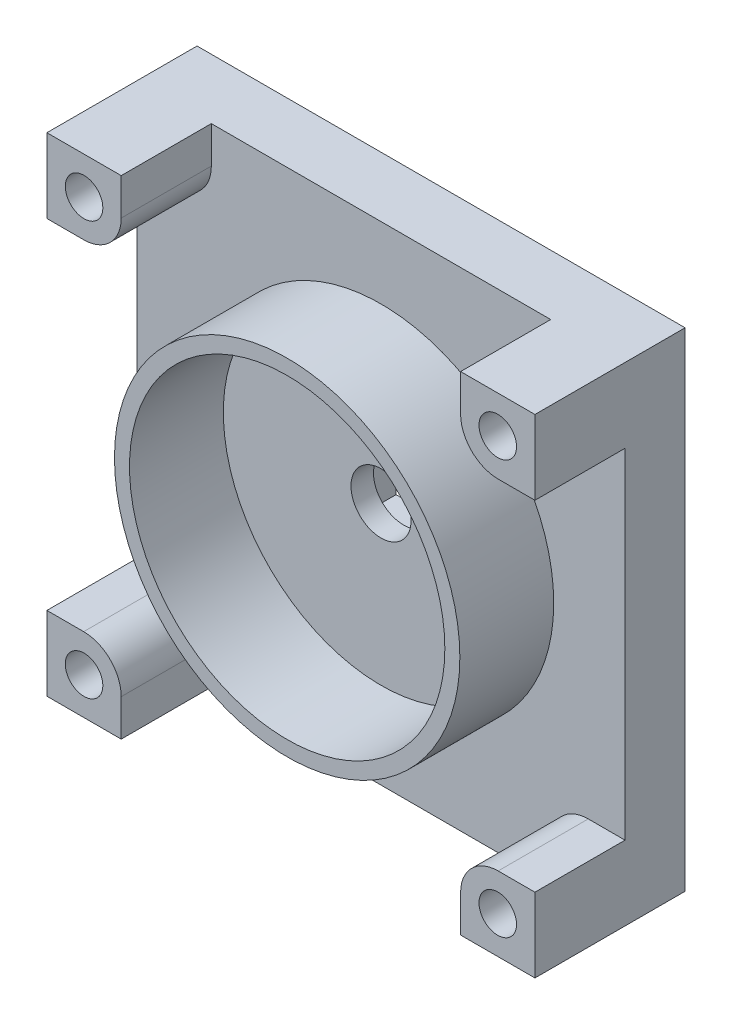
SolidWorks part; units mm, degrees
ref_plane "Alzado" through (0, 0, 0) normal (0, 0, 1) x (1, 0, 0)
ref_plane "Planta" through (0, 0, 0) normal (0, 1, 0) x (1, 0, 0)
ref_plane "Vista lateral" through (0, 0, 0) normal (1, 0, 0) x (0, 0, -1)
sketch "Croquis1" plane through (0, 0, 0) normal (0, 0, 1) x (1, 0, 0)
  circle A0 centre (0, 0) radius 21
  circle A1 centre (0, 0) radius 23
  dimension "D1" = 42
  dimension "D2" = 46
extrude "Saliente-Extruir1" add sketch "Croquis1" along normal blind 12.5
sketch "Croquis2" plane through (0, 0, 0) normal (0, 0, 1) x (1, 0, 0)
  line L1 (-32.5, -32.5) -> (32.5, -32.5)
  line L2 (-32.5, -32.5) -> (-32.5, 32.5)
  line L3 (-32.5, 32.5) -> (32.5, 32.5)
  line L4 (32.5, -32.5) -> (32.5, 32.5)
  line L5 (-32.5, -32.5) -> (32.5, 32.5) construction
  line L6 (-32.5, 32.5) -> (32.5, -32.5) construction
  circle A0 centre (-27.5503, 27.5503) radius 2.5
  circle A1 centre (27.5503, 27.5503) radius 2.5
  circle A2 centre (-27.5503, -27.5503) radius 2.5
  circle A3 centre (27.5503, -27.5503) radius 2.5
  point P0 (0, 0)
  dimension "D2" = 5
  dimension "D1" = 65
  dimension "D3" = 7
extrude "Saliente-Extruir2" add sketch "Croquis2" against normal blind 8
sketch "Croquis3" plane through (0, 0, -8) normal (0, 0, -1) x (-1, 0, 0)
  line L1 (-6, -6) -> (6, -6)
  line L2 (-6, -6) -> (-6, 6)
  line L3 (-6, 6) -> (6, 6)
  line L4 (6, -6) -> (6, 6)
  line L5 (-6, -6) -> (6, 6) construction
  line L6 (-6, 6) -> (6, -6) construction
  point P0 (0, 0)
  dimension "D1" = 12
extrude "Cortar-Extruir1" cut sketch "Croquis3" against normal blind 5
sketch "Croquis4" plane through (0, 0, -3) normal (0, 0, -1) x (-1, 0, 0)
  circle A0 centre (0, 0) radius 4
  dimension "D1" = 8
extrude "Cortar-Extruir2" cut sketch "Croquis4" against normal up to next
sketch "Croquis5" plane through (0, 0, 0) normal (0, 0, 1) x (1, 0, 0)
  line L1 (27.6005, 22.6005) -> (32.5, 22.6005)
  line L2 (22.6005, 27.6005) -> (22.6005, 32.5)
  line L3 (22.6005, 32.5) -> (32.5, 32.5)
  line L4 (32.5, 22.6005) -> (32.5, 32.5)
  line L5 (22.6005, 22.6005) -> (32.5, 32.5) construction
  line L6 (22.6005, 32.5) -> (32.5, 22.6005) construction
  line L7 (-27.6005, 22.6005) -> (-32.5, 22.6005)
  line L8 (-22.6005, 27.6005) -> (-22.6005, 32.5)
  line L9 (-22.6005, 32.5) -> (-32.5, 32.5)
  line L10 (-32.5, 22.6005) -> (-32.5, 32.5)
  line L11 (-22.6005, 22.6005) -> (-32.5, 32.5) construction
  line L12 (-22.6005, 32.5) -> (-32.5, 22.6005) construction
  line L13 (-27.6005, -22.6005) -> (-32.5, -22.6005)
  line L14 (-22.6005, -27.6005) -> (-22.6005, -32.5)
  line L15 (-22.6005, -32.5) -> (-32.5, -32.5)
  line L16 (-32.5, -22.6005) -> (-32.5, -32.5)
  line L17 (-22.6005, -22.6005) -> (-32.5, -32.5) construction
  line L18 (-22.6005, -32.5) -> (-32.5, -22.6005) construction
  line L19 (27.6005, -22.6005) -> (32.5, -22.6005)
  line L20 (22.6005, -27.6005) -> (22.6005, -32.5)
  line L21 (22.6005, -32.5) -> (32.5, -32.5)
  line L22 (32.5, -22.6005) -> (32.5, -32.5)
  line L23 (22.6005, -22.6005) -> (32.5, -32.5) construction
  line L24 (22.6005, -32.5) -> (32.5, -22.6005) construction
  arc A0 (-27.6005, 22.6005) -> (-22.6005, 27.6005) centre (-27.6005, 27.6005) ccw
  arc A1 (27.6005, 22.6005) -> (22.6005, 27.6005) centre (27.6005, 27.6005) cw
  arc A2 (27.6005, -22.6005) -> (22.6005, -27.6005) centre (27.6005, -27.6005) ccw
  arc A3 (-27.6005, -22.6005) -> (-22.6005, -27.6005) centre (-27.6005, -27.6005) cw
  circle A4 centre (-27.5503, -27.5503) radius 2.5 construction
  circle A5 centre (27.5503, -27.5503) radius 2.5 construction
  circle A6 centre (27.5503, 27.5503) radius 2.5 construction
  circle A7 centre (-27.5503, 27.5503) radius 2.5 construction
  circle A8 centre (-27.5503, -27.5503) radius 2.5
  circle A9 centre (27.5503, -27.5503) radius 2.5
  circle A10 centre (27.5503, 27.5503) radius 2.5
  circle A11 centre (-27.5503, 27.5503) radius 2.5
  point P0 (27.5503, 27.5503)
  point P5 (-27.5503, 27.5503)
  point P12 (-27.5503, -27.5503)
  point P19 (27.5503, -27.5503)
  dimension "D1" = 5
  dimension "D2" = 5
extrude "Saliente-Extruir3" add sketch "Croquis5" along normal blind 12
